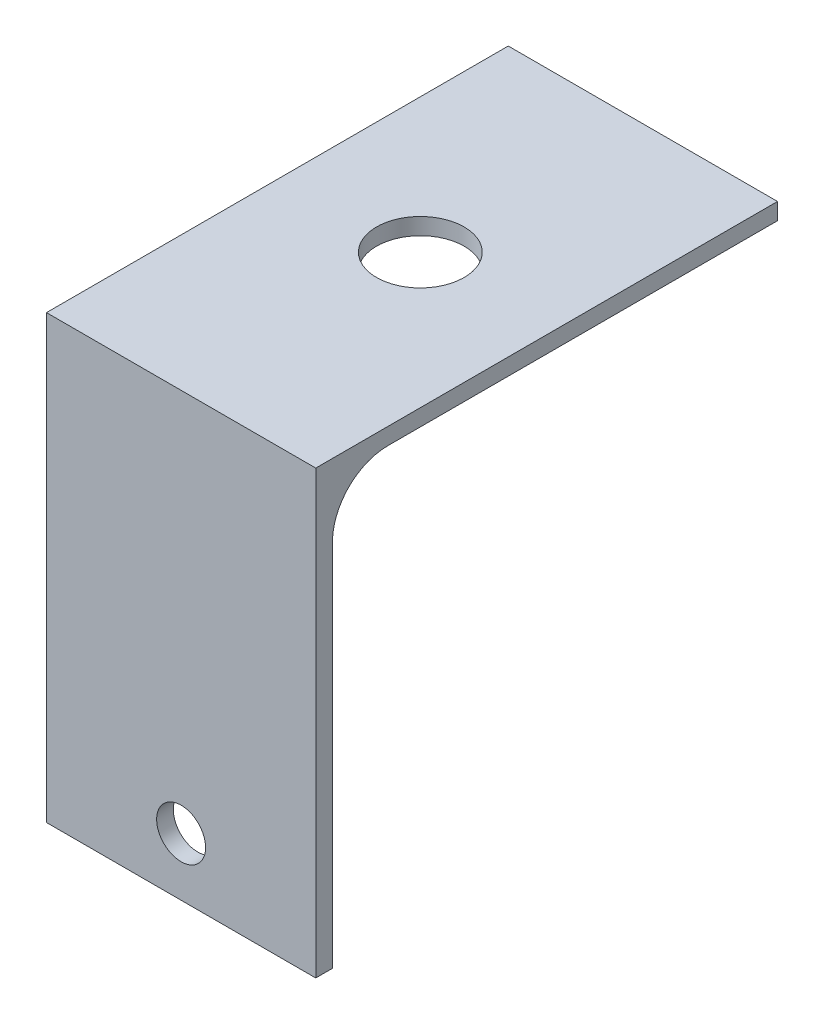
SolidWorks part; units mm, degrees
material "1060 Alloy"
ref_plane "Front Plane" through (0, 0, 0) normal (0, 0, 1) x (1, 0, 0)
ref_plane "Top Plane" through (0, 0, 0) normal (0, 1, 0) x (1, 0, 0)
ref_plane "Right Plane" through (0, 0, 0) normal (1, 0, 0) x (0, 0, -1)
sketch "Sketch1" plane through (0, 0, 0) normal (0, 0, 1) x (1, 0, 0)
  line L1 (12.1, -19.845) -> (-12.1, -19.845)
  line L2 (12.1, -19.845) -> (12.1, 19.845)
  line L3 (12.1, 19.845) -> (-12.1, 19.845)
  line L4 (-12.1, -19.845) -> (-12.1, 19.845)
  line L5 (12.1, -19.845) -> (-12.1, 19.845) construction
  line L6 (12.1, 19.845) -> (-12.1, -19.845) construction
  point P0 (0, 0)
  dimension "Base" = 24.2
  dimension "ServoToTop" = 39.69
extrude "Boss-Extrude1" add sketch "Sketch1" along normal blind 1.5
sketch "Sketch2" plane through (0, 0, 1.5) normal (0, 0, 1) x (1, 0, 0)
  line L0 (-12.1, -19.845) -> (12.1, -19.845) construction
  line L1 (12.1, -19.845) -> (12.1, 19.845) construction
  circle A0 centre (0, -14.645) radius 2.2
  dimension "D2" = 4.4
  dimension "D1" = 5.2
  dimension "D3" = 12.1
extrude "Cut-Extrude1" cut sketch "Sketch2" against normal through all
sketch "Sketch4" plane through (0, 19.845, 0) normal (0, 1, 0) x (1, 0, 0)
  line L0 (-12.1, -1.5) -> (-12.1, 0) construction
  line L1 (-12.1, 0) -> (12.1, 0)
  line L2 (-12.1, 0) -> (-12.1, 40)
  line L3 (-12.1, 40) -> (12.1, 40)
  line L4 (12.1, 0) -> (12.1, 40)
  line L5 (12.1, -1.5) -> (12.1, 0) construction
  dimension "BaseTopLength" = 40
extrude "Boss-Extrude2" add sketch "Sketch4" against normal blind 1.5
sketch "Sketch5" plane through (0, 18.345, 0) normal (0, -1, 0) x (1, 0, 0)
  line L0 (-12.1, 0) -> (12.1, 0) construction
  line L1 (-12.1, -40) -> (-12.1, 0) construction
  circle A0 centre (0, -20) radius 3.937
  dimension "D1" = 7.874
  dimension "D2" = 20
  dimension "D3" = 12.1
extrude "Cut-Extrude2" cut sketch "Sketch5" against normal through all
fillet "Fillet1" radius 5 1 edges at (0, 18.345, 0)
